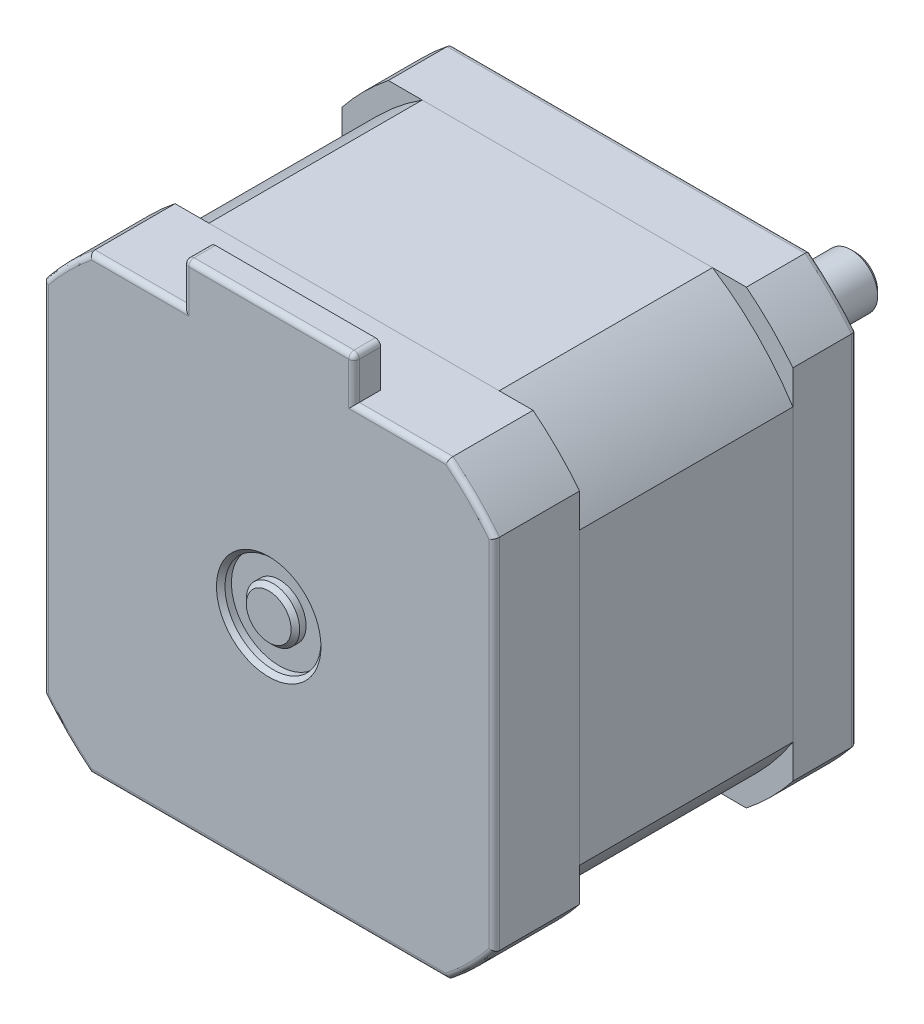
SolidWorks part; units mm, degrees
ref_plane "Plan de face" through (0, 0, 0) normal (0, 0, 1) x (1, 0, 0)
ref_plane "Plan de dessus" through (0, 0, 0) normal (0, 1, 0) x (1, 0, 0)
ref_plane "Plan de droite" through (0, 0, 0) normal (1, 0, 0) x (0, 0, -1)
sketch "Esquisse1" plane through (0, 0, 0) normal (0, 0, 1) x (1, 0, 0)
  line L0 (21.15, 16.7833) -> (21.15, -16.7833)
  line L1 (-21.15, 21.15) -> (21.15, 21.15) construction
  line L2 (-21.15, 21.15) -> (-21.15, -21.15) construction
  line L3 (-21.15, -21.15) -> (21.15, -21.15) construction
  line L4 (21.15, 21.15) -> (21.15, -21.15) construction
  line L5 (-21.15, 21.15) -> (21.15, -21.15) construction
  line L6 (-21.15, -21.15) -> (21.15, 21.15) construction
  line L7 (16.7833, -21.15) -> (-16.7833, -21.15)
  line L8 (-21.15, -16.7833) -> (-21.15, 16.7833)
  line L9 (-16.7833, 21.15) -> (16.7833, 21.15)
  arc A0 (-16.7833, 21.15) -> (-21.15, 16.7833) centre (0, 0) ccw
  arc A1 (21.15, 16.7833) -> (16.7833, 21.15) centre (0, 0) ccw
  arc A2 (-21.15, -16.7833) -> (-16.7833, -21.15) centre (0, 0) ccw
  arc A3 (16.7833, -21.15) -> (21.15, -16.7833) centre (0, 0) ccw
  point P0 (0, 0)
  dimension "D2" = 54
  dimension "D1" = 42.3
extrude "Boss.-Extru.1" add sketch "Esquisse1" along normal blind 6
sketch "Esquisse2" plane through (0, 0, 6) normal (0, 0, 1) x (1, 0, 0)
  line L23 (-13.6088, 21.15) -> (13.6088, 21.15)
  line L24 (16.7833, 21.15) -> (-16.7833, 21.15) construction
  line L25 (21.15, 13.6088) -> (21.15, -13.6088)
  line L26 (21.15, -16.7833) -> (21.15, 16.7833) construction
  line L27 (13.6088, -21.15) -> (-13.6088, -21.15)
  line L28 (-16.7833, -21.15) -> (16.7833, -21.15) construction
  line L29 (-21.15, -13.6088) -> (-21.15, 13.6088)
  line L30 (-21.15, 16.7833) -> (-21.15, -16.7833) construction
  arc A60 (-13.6088, 21.15) -> (-21.15, 13.6088) centre (0, 0) ccw
  arc A61 (21.15, 16.7833) -> (16.7833, 21.15) centre (0, 0) ccw construction
  arc A62 (21.15, 13.6088) -> (13.6088, 21.15) centre (0, 0) ccw
  arc A63 (13.6088, -21.15) -> (21.15, -13.6088) centre (0, 0) ccw
  arc A64 (-21.15, -13.6088) -> (-13.6088, -21.15) centre (0, 0) ccw
  dimension "D1" = 1.85
extrude "Boss.-Extru.2" add sketch "Esquisse2" along normal blind 20 separate body
sketch "Esquisse3" plane through (0, 0, 26) normal (0, 0, 1) x (1, 0, 0)
  line L0 (-16.7833, -21.15) -> (16.7833, -21.15) construction
  line L1 (21.15, -16.7833) -> (21.15, 16.7833) construction
  line L2 (16.7833, 21.15) -> (-16.7833, 21.15) construction
  line L3 (-21.15, 16.7833) -> (-21.15, -16.7833) construction
  line L4 (-16.7833, -21.15) -> (16.7833, -21.15)
  line L5 (21.15, -16.7833) -> (21.15, 16.7833)
  line L6 (16.7833, 21.15) -> (-16.7833, 21.15)
  line L7 (-21.15, 16.7833) -> (-21.15, -16.7833)
  arc A0 (-21.15, -16.7833) -> (-16.7833, -21.15) centre (0, 0) ccw construction
  arc A1 (16.7833, -21.15) -> (21.15, -16.7833) centre (0, 0) ccw construction
  arc A2 (21.15, 16.7833) -> (16.7833, 21.15) centre (0, 0) ccw construction
  arc A3 (-16.7833, 21.15) -> (-21.15, 16.7833) centre (0, 0) ccw construction
  arc A4 (-21.15, -16.7833) -> (-16.7833, -21.15) centre (0, 0) ccw
  arc A5 (16.7833, -21.15) -> (21.15, -16.7833) centre (0, 0) ccw
  arc A6 (21.15, 16.7833) -> (16.7833, 21.15) centre (0, 0) ccw
  arc A7 (-16.7833, 21.15) -> (-21.15, 16.7833) centre (0, 0) ccw
extrude "Boss.-Extru.3" add sketch "Esquisse3" along normal blind 8 separate body
sketch "Esquisse4" plane through (0, 21.15, 0) normal (0, 1, 0) x (1, 0, 0)
  line L0 (16.7833, -34) -> (-16.7833, -34) construction
  line L1 (8, -34) -> (-8, -34)
  line L2 (8, -34) -> (8, -31.5)
  line L3 (8, -31.5) -> (-8, -31.5)
  line L4 (-8, -34) -> (-8, -31.5)
  line L5 (0, 0) -> (0, -31.5) construction
  dimension "D1" = 2.5
  dimension "D2" = 16
extrude "Boss.-Extru.4" add sketch "Esquisse4" along normal blind 4
sketch "Esquisse5" plane through (0, 0, 0) normal (1, 0, 0) x (0, 0, -1)
  line L0 (0, 0) -> (-78.698, 0) construction
  line L2 (2, 11) -> (0, 11)
  line L3 (2, 11) -> (2, 4.5)
  line L4 (2, 4.5) -> (0, 4.5)
  line L5 (0, 11) -> (0, 4.5)
  line L6 (0, -16.7833) -> (0, 16.7833) construction
  line L7 (21, 0) -> (0, 0)
  line L8 (21, 0) -> (21, 2.5)
  line L9 (21, 2.5) -> (0, 2.5)
  line L10 (0, 0) -> (0, 2.5)
  dimension "D1" = 2
  dimension "D2" = 22
  dimension "D3" = 9
  dimension "D4" = 5
  dimension "D5" = 21
revolve "Révolution1" add sketch "Esquisse5" angle 360 about L0
fillet "Congé1" radius 0.5 14 edges at (-21.15, 0, 34) (-19.0919, 19.0919, 34) (-12.3916, 21.15, 34) (-8, 23.15, 34) (0, 25.15, 34) (8, 23.15, 34) (12.3916, 21.15, 34) (19.0919, 19.0919, 34) (21.15, 0, 34) (19.0919, -19.0919, 34) (0, -21.15, 34) (-19.0919, -19.0919, 34) (-8, 25.15, 32.75) (8, 25.15, 32.75)
fillet "Congé2" radius 0.5 8 edges at (-19.0919, 19.0919, 0) (-21.15, 0, 0) (-19.0919, -19.0919, 0) (0, -21.15, 0) (19.0919, -19.0919, 0) (21.15, 0, 0) (0, 21.15, 0) (19.0919, 19.0919, 0)
chamfer "Chanfrein1" distance 0.4 angle 45 1 edges at (-2.5, 0, -21)
chamfer "Chanfrein2" distance 0.4 angle 45 1 edges at (-4.5, 0, -2)
sketch "Esquisse6" plane through (0, 0, 0) normal (0, 1, 0) x (0, 0, -1)
  line L0 (0, -2.5) -> (20.6, -2.5) construction
  line L1 (21, 2.5) -> (3, 2.5)
  line L2 (21, 2.5) -> (21, 2)
  line L3 (21, 2) -> (3, 2)
  line L4 (3, 2.5) -> (3, 2)
  line L5 (21, -2.1) -> (21, 2.1) construction
  line L6 (20.6, 2.5) -> (0, 2.5) construction
  dimension "D1" = 4.5
  dimension "D2" = 18
extrude "Enlèv. mat.-Extru.1" cut sketch "Esquisse6" against normal through all both and the other way through all
sketch "Esquisse7" plane through (0, 0, 34) normal (0, 0, 1) x (1, 0, 0)
  circle A0 centre (0, 0) radius 2.5
  circle A1 centre (0, 0) radius 4.5
  dimension "D1" = 5
  dimension "D2" = 9
extrude "Enlèv. mat.-Extru.2" cut sketch "Esquisse7" against normal blind 1
chamfer "Chanfrein3" distance 0.4 angle 45 2 edges at (4.5, 0, 34) (2.5, 0, 34)
hole_wizard "Trou taraudé M31" positions "Esquisse8" profile "Esquisse9" tap size "M3" standard "ISO"
sketch "Esquisse8" plane through (0, 0, 0) normal (0, 0, -1) x (-1, 0, 0)
  line L0 (-15.5, 15.5) -> (15.5, 15.5) construction
  line L1 (15.5, 15.5) -> (15.5, -15.5) construction
  line L2 (15.5, -15.5) -> (-15.5, -15.5) construction
  line L3 (-15.5, -15.5) -> (-15.5, 15.5) construction
  circle A0 centre (0, 0) radius 21.9203 construction
  point P5 (-15.5, 15.5)
  point P6 (15.5, 15.5)
  point P7 (15.5, -15.5)
  point P8 (-15.5, -15.5)
  dimension "D1" = 31
sketch "Esquisse9" plane through (15.5, -15.5, 0) normal (1, 0, 0) x (0, 1, 0)
  line L0 (0, 0) -> (0, 5.7511)
  line L1 (0, 5.7511) -> (1.25, 5)
  line L2 (1.25, 5) -> (1.25, 0)
  line L5 (1.25, 0) -> (0, 0)
  line L10 (0, 5.7511) -> (-1.25, 5) construction
  line L11 (0, -6.35) -> (0, 107.95) construction
  dimension "Diamètre du trou pour taraudage" = 2.5
  dimension "Profondeur du trou pour taraudage" = 5
  dimension "Angle de pointe" = 118
cosmetic thread "Filetage de perçage1" parameters "D1"=5, "D2"=3
cosmetic thread "Filetage de perçage2" parameters "D1"=5, "D2"=3
cosmetic thread "Filetage de perçage3" parameters "D1"=5, "D2"=3
cosmetic thread "Filetage de perçage4" parameters "D1"=5, "D2"=3
sketch "Sketch1" plane through (0, 0, -21) normal (0, 0, -1) x (-1, 0, 0)
  point P0 (0, 0)
